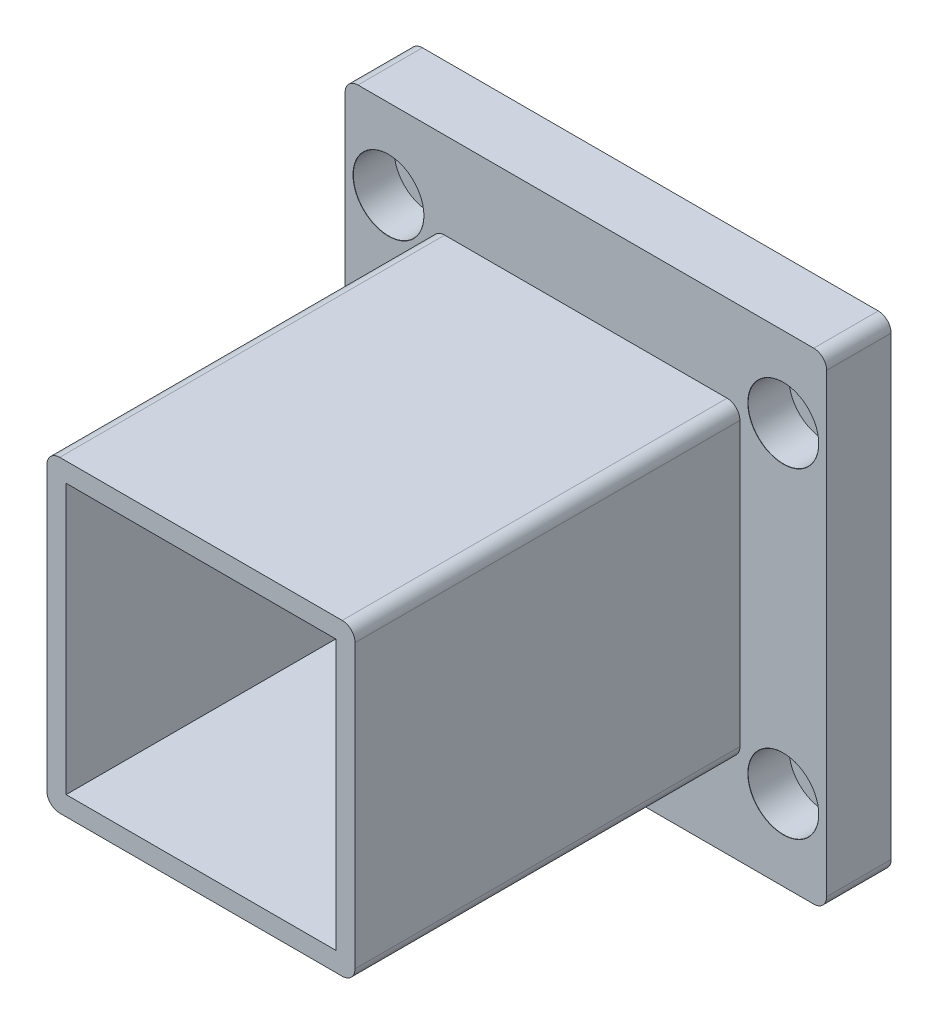
SolidWorks part; units mm, degrees
ref_plane "Front Plane" through (0, 0, 0) normal (1, 0, 0) x (0, 1, 0)
ref_plane "Top Plane" through (0, 0, 0) normal (0, 0, 1) x (0, 1, 0)
ref_plane "Right Plane" through (0, 0, 0) normal (0, 1, 0) x (-1, 0, 0)
sketch "Sketch1" plane through (0, 0, 0) normal (0, 0, 1) x (0, 1, 0)
  line L0 (-25.048, 30.1461) -> (-26.1566, 30.1461)
  line L1 (-25.048, 30.1461) -> (22.952, 30.1461)
  line L2 (-25.048, 30.1461) -> (-25.048, -17.8539)
  line L3 (-25.048, -17.8539) -> (22.952, -17.8539)
  line L4 (22.952, 30.1461) -> (22.952, -17.8539)
  line L6 (22.952, 30.1461) -> (15.3397, 30.1461)
  line L8 (-22.048, 27.1461) -> (-22.048, -14.8539)
  line L9 (-22.048, -14.8539) -> (19.952, -14.8539)
  line L10 (19.952, 27.1461) -> (19.952, -14.8539)
  line L11 (-22.048, 27.1461) -> (19.952, 27.1461)
  dimension "D1" = 42
  dimension "D2" = 42
  dimension "D3" = 3
extrude "Boss-Extrude1" add sketch "Sketch1" along normal blind 65 contours L4 L1 L0 L2 L3 L8 L11 L10 L9
sketch "Sketch3" plane through (0, 0, 0) normal (0, 0, -1) x (1, 0, 0)
  line L0 (-6.1461, 25.048) -> (-6.1461, -22.952)
  line L1 (-30.1461, 25.048) -> (17.8539, 25.048) construction
  line L2 (-30.1461, -22.952) -> (17.8539, -22.952) construction
  line L3 (17.8539, 25.048) -> (31.3539, 38.548)
  line L4 (-43.6461, 38.548) -> (31.3539, 38.548)
  line L5 (-43.6461, 38.548) -> (-43.6461, -36.452)
  line L6 (-43.6461, -36.452) -> (31.3539, -36.452)
  line L7 (31.3539, 38.548) -> (31.3539, -36.452)
  line L8 (-43.6461, 38.548) -> (31.3539, -36.452) construction
  line L9 (-43.6461, -36.452) -> (31.3539, 38.548) construction
  line L10 (24.6039, -23.952) -> (24.6039, 26.048)
  line L11 (24.6039, -29.702) -> (24.6039, 31.798)
  line L12 (-31.1461, 31.798) -> (18.8539, 31.798)
  line L13 (-36.8961, -23.952) -> (-36.8961, 26.048)
  line L14 (18.8539, -29.702) -> (-31.1461, -29.702)
  point P6 (-6.1461, 1.048)
  point P22 (24.6039, 1.048)
  dimension "D1" = 50
  dimension "D2" = 75
extrude "Boss-Extrude2" add sketch "Sketch3" along normal blind 5
sketch "Sketch8" plane through (0, 0, 0) normal (0, 0, 1) x (1, 0, 0)
  line L1 (-43.6461, 36.452) -> (31.3539, 36.452)
  line L2 (-43.6461, 36.452) -> (-43.6461, -38.548)
  line L3 (-43.6461, -38.548) -> (31.3539, -38.548)
  line L4 (31.3539, 36.452) -> (31.3539, -38.548)
  line L5 (-27.1461, 19.952) -> (14.8539, 19.952)
  line L6 (-27.1461, 19.952) -> (-27.1461, -22.048)
  line L7 (-27.1461, -22.048) -> (14.8539, -22.048)
  line L8 (14.8539, 19.952) -> (14.8539, -22.048)
  point P10 (0, 0)
  point P12 (0, 0)
extrude "Boss-Extrude3" add sketch "Sketch8" along normal blind 5.0471
fillet "Fillet1" radius 2 8 edges at (17.8539, -25.048, 35.0235) (17.8539, 22.952, 35.0235) (31.3539, 36.452, 0.0235) (-43.6461, 36.452, 0.0235) (-43.6461, -38.548, 0.0235) (31.3539, -38.548, 0.0235) (-30.1461, 22.952, 35.0235) (-30.1461, -25.048, 35.0235)
sketch "Sketch13" plane through (0, 0, 5.0471) normal (0, 0, 1) x (1, 0, 0)
  line L0 (-36.8961, 23.952) -> (-36.8961, -26.048)
  line L1 (-31.1461, -31.798) -> (18.8539, -31.798)
  line L2 (-43.6461, 36.452) -> (31.3539, -38.548)
  line L3 (24.6039, 23.952) -> (24.6039, -26.048)
  line L4 (-31.1461, 29.702) -> (18.8539, 29.702)
  point P0 (-36.8961, 23.952)
  point P1 (-36.8961, -26.048)
  point P12 (24.6039, 23.952)
  point P13 (24.6039, -26.048)
hole_wizard "CBORE for M6 Hex Socket Head Cap Screw2" positions "Sketch13" profile "Sketch15" counterbore size "M6" standard "ISO" end condition through all
sketch "Sketch15" plane through (-36.8961, 23.952, 5.0471) normal (1, 0, 0) x (0, -1, 0)
  line L0 (0, 0) -> (0, 10.0471)
  line L1 (0, 10.0471) -> (3.3, 10.0471)
  line L3 (3.3, 10.0471) -> (3.3, 6.4)
  line L4 (5.5, 6.4) -> (3.3, 6.4)
  line L5 (5.5, 6.4) -> (5.5, 0.025)
  line L6 (5.5, 0.025) -> (5.525, 0)
  line L7 (5.525, 0) -> (0, 0)
  line L8 (-5.5, 0.025) -> (-5.525, 0) construction
  line L11 (0, -6.35) -> (0, 107.95) construction
  dimension "Thru Hole Dia." = 6.6
  dimension "Thru Hole Depth" = 10.0471
  dimension "C'Bore Dia." = 11
  dimension "C'Bore Depth" = 6.4
  dimension "Near C'Sink Dia." = 11.05
  dimension "Near C'Sink Angle" = 90
